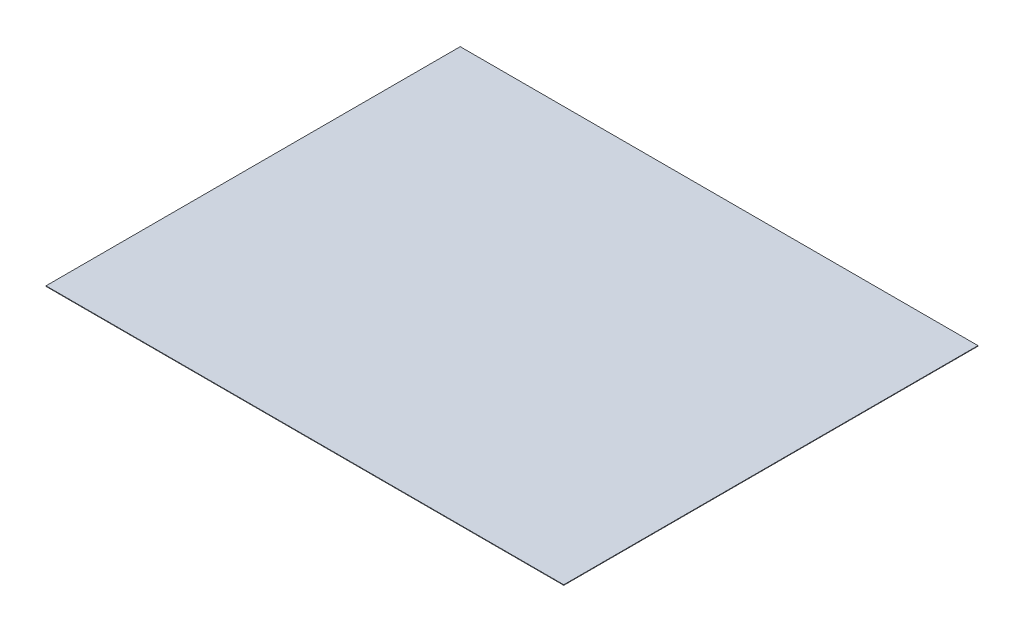
SolidWorks part; units mm, degrees
ref_plane "前视基准面" through (0, 0, 0) normal (0, 0, 1) x (1, 0, 0)
ref_plane "上视基准面" through (0, 0, 0) normal (0, 1, 0) x (1, 0, 0)
ref_plane "右视基准面" through (0, 0, 0) normal (1, 0, 0) x (0, 0, -1)
sketch "草图1" plane through (0, 0, 0) normal (0, 1, 0) x (1, 0, 0)
  line L1 (-50, 40) -> (50, 40)
  line L2 (-50, 40) -> (-50, -40)
  line L3 (-50, -40) -> (50, -40)
  line L4 (50, 40) -> (50, -40)
  line L5 (-50, 40) -> (50, -40) construction
  line L6 (-50, -40) -> (50, 40) construction
  point P0 (0, 0)
  dimension "D1" = 80
  dimension "D2" = 100
extrude "凸台-拉伸1" add sketch "草图1" along normal blind 0.1
